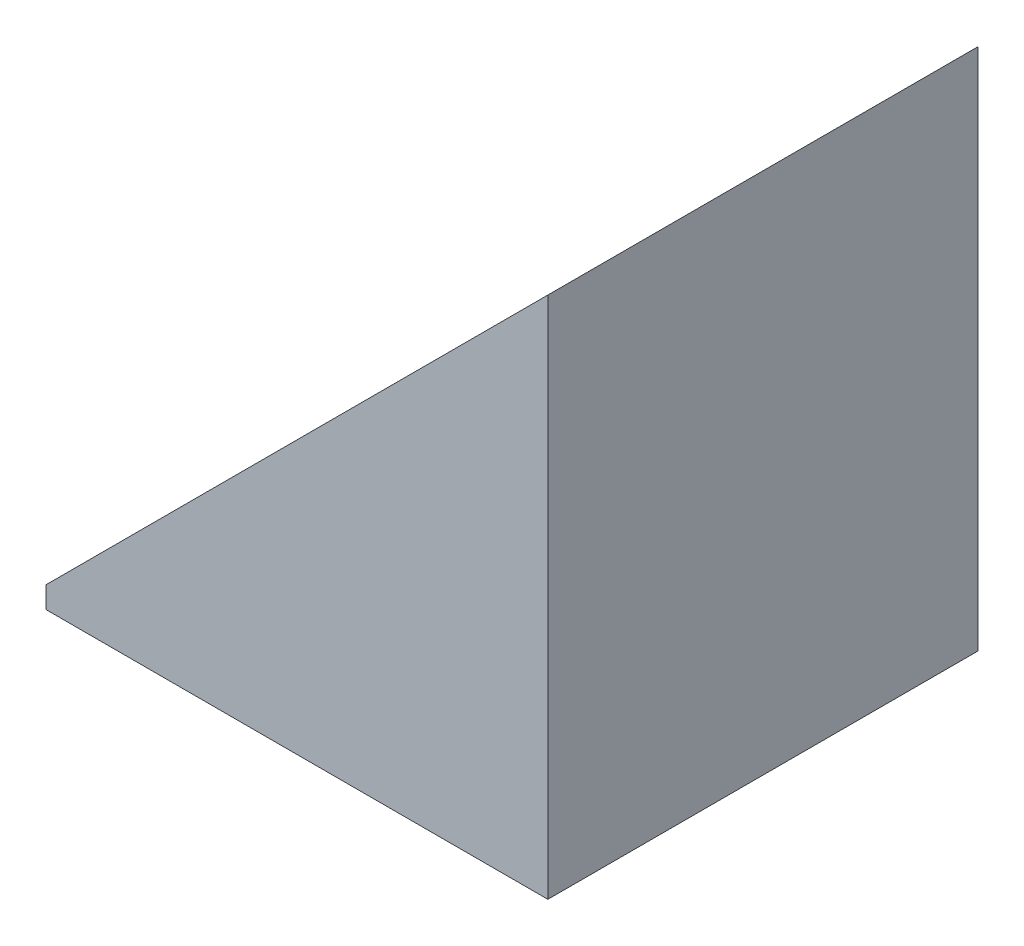
SolidWorks part; units mm, degrees
ref_plane "前视基准面" through (0, 0, 0) normal (0, 0, 1) x (1, 0, 0)
ref_plane "上视基准面" through (0, 0, 0) normal (0, 1, 0) x (1, 0, 0)
ref_plane "右视基准面" through (0, 0, 0) normal (1, 0, 0) x (0, 0, -1)
other "Configuration Table"
sketch "草图1" plane through (0, 0, 0) normal (0, 0, 1) x (1, 0, 0)
  line L0 (0, 0) -> (70, 0)
  line L1 (70, 0) -> (70, 73)
  line L2 (70, 73) -> (0, 3)
  line L3 (0, 3) -> (0, 0)
extrude "凸台-拉伸1" add sketch "草图1" along normal blind 60
sketch "草图2" plane through (-1.5, 1.5, 0) normal (-0.7071, 0.7071, 0) x (0, 0, 1)
  circle A0 centre (19.503, 42.4978) radius 0.85
  circle A1 centre (23.123, 63.5058) radius 0.85
  circle A2 centre (40.502, 59.0788) radius 0.85
  circle A3 centre (37.391, 40.8778) radius 0.85
extrude "切除-拉伸1" cut sketch "草图2" against normal mid plane 60
